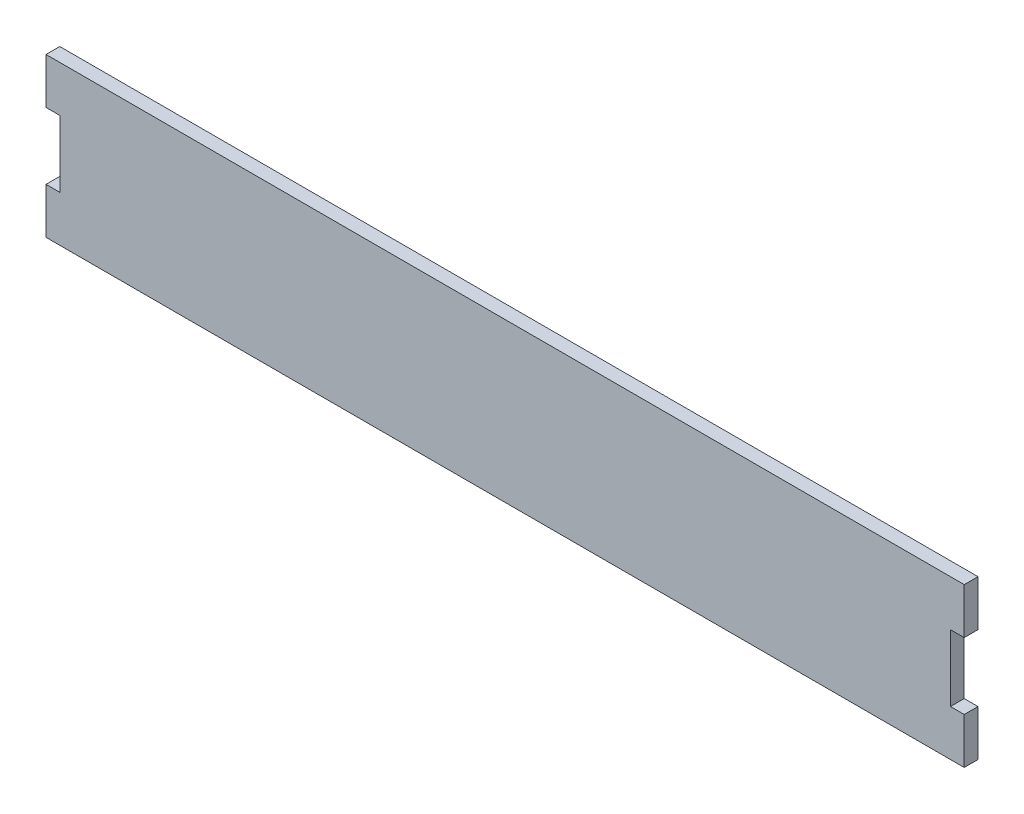
SolidWorks part; units mm, degrees
ref_plane "正面" through (0, 0, 0) normal (0, 0, 1) x (1, 0, 0)
ref_plane "平面" through (0, 0, 0) normal (0, 1, 0) x (1, 0, 0)
ref_plane "右側面" through (0, 0, 0) normal (1, 0, 0) x (0, 0, -1)
sketch "ｽｹｯﾁ1" plane through (0, 0, 0) normal (0, 0, 1) x (1, 0, 0)
  line L0 (0, 0) -> (0, 10)
  line L1 (0, 0) -> (200, 0)
  line L2 (0, 10) -> (3, 10)
  line L3 (0, 34.5) -> (200, 34.5)
  line L4 (200, 34.5) -> (200, 24.5)
  line L5 (0, 34.5) -> (0, 24.5)
  line L6 (0, 24.5) -> (3, 24.5)
  line L7 (3, 24.5) -> (3, 10)
  line L8 (200, 24.5) -> (197, 24.5)
  line L9 (197, 24.5) -> (197, 10)
  line L10 (197, 10) -> (200, 10)
  line L11 (200, 10) -> (200, 0)
extrude "ﾎﾞｽ - 押し出し1" add sketch "ｽｹｯﾁ1" along normal blind 3
